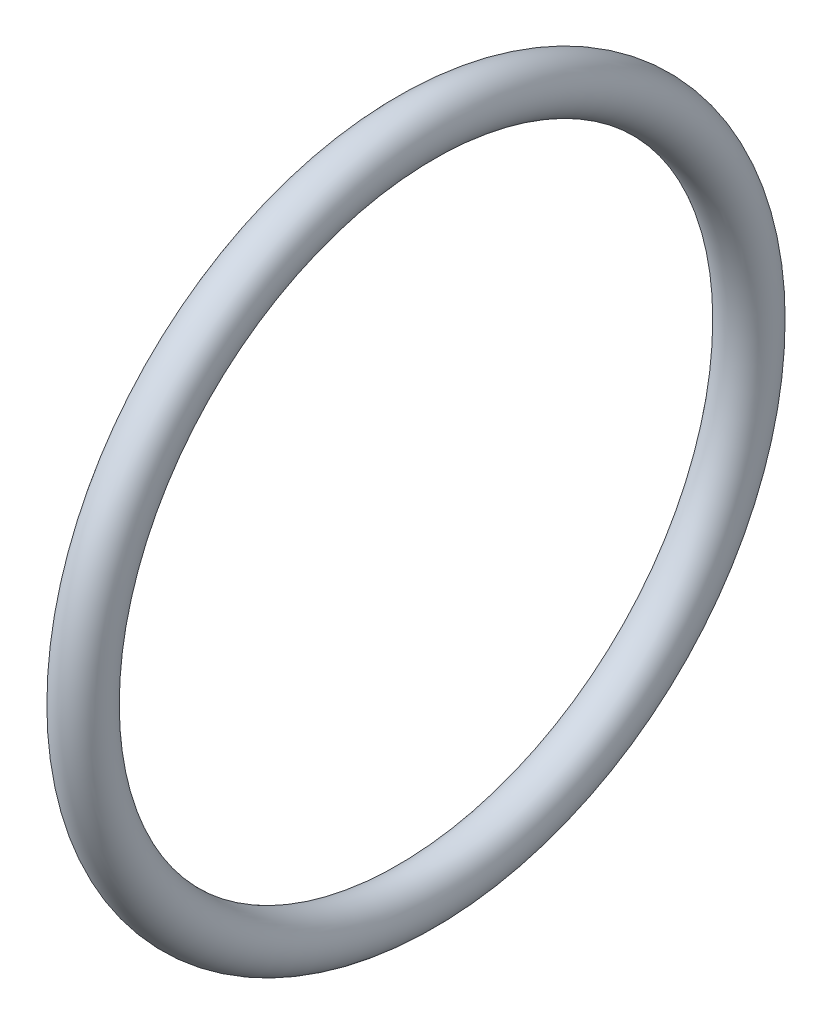
SolidWorks part; units mm, degrees
ref_plane "Front Plane" through (0, 0, 0) normal (0, 0, 1) x (1, 0, 0)
ref_plane "Top Plane" through (0, 0, 0) normal (0, 1, 0) x (1, 0, 0)
ref_plane "Right Plane" through (0, 0, 0) normal (1, 0, 0) x (0, 0, -1)
sketch "Sketch1" plane through (0, 0, 0) normal (0, 0, 1) x (1, 0, 0)
  line L0 (0, 0) -> (0, 88.9) construction
  line L1 (0, 82.55) -> (0, 88.9) construction
  line L2 (0, 0) -> (42.6124, 0) construction
  circle A0 centre (0, 82.55) radius 6.35
  dimension "D2" = 12.7
  dimension "D1" = 88.9
revolve "Revolve1" add sketch "Sketch1" angle 360 about L2
sketch "Sketch2" plane through (0, 0, 0) normal (1, 0, 0) x (0, 0, -1)
  circle A0 centre (0, 0) radius 26.6378 construction
